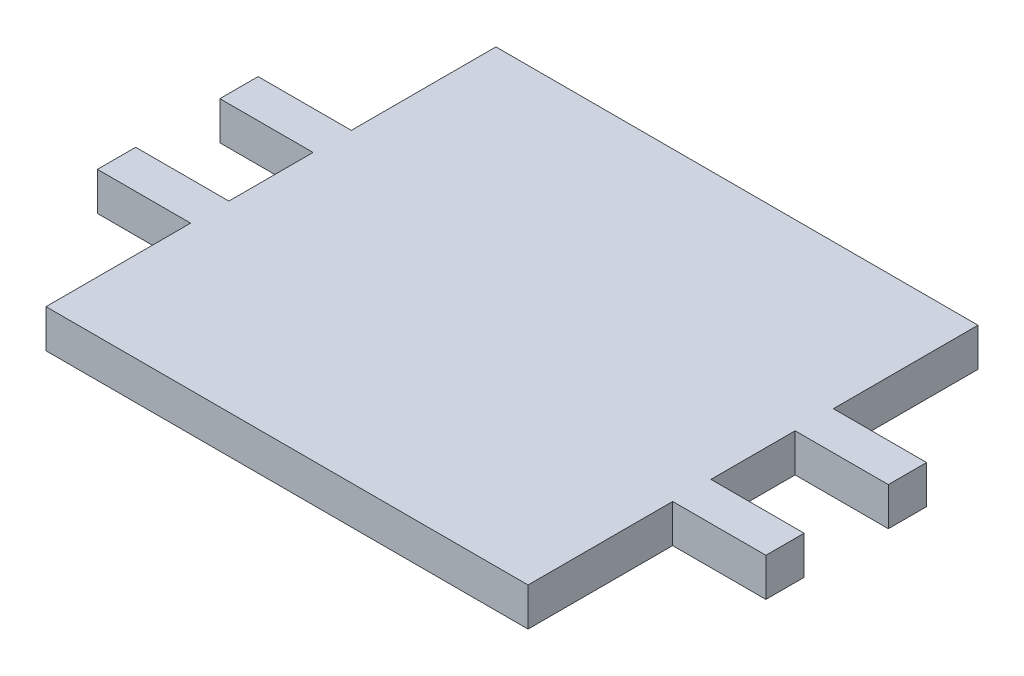
SolidWorks part; units mm, degrees
ref_plane "Front Plane" through (0, 0, 0) normal (0, 0, 1) x (1, 0, 0)
ref_plane "Top Plane" through (0, 0, 0) normal (0, 1, 0) x (1, 0, 0)
ref_plane "Right Plane" through (0, 0, 0) normal (1, 0, 0) x (0, 0, -1)
sketch "Sketch1" plane through (0, 0, 0) normal (0, 1, 0) x (1, 0, 0)
  line L0 (0, 35.56) -> (0, -35.56) construction
  line L1 (-38.1, 35.56) -> (38.1, 35.56)
  line L2 (-38.1, 35.56) -> (-38.1, -35.56)
  line L3 (-38.1, -35.56) -> (38.1, -35.56)
  line L4 (38.1, 35.56) -> (38.1, -35.56)
  line L5 (-38.1, 0) -> (38.1, 0) construction
  line L6 (-52.832, 6.6548) -> (-52.832, -6.6548) construction
  line L7 (-52.832, 12.7) -> (-38.1, 12.7)
  line L8 (-52.832, 12.7) -> (-52.832, 6.6548)
  line L9 (-52.832, 6.6548) -> (-38.1, 6.6548)
  line L10 (-38.1, 12.7) -> (-38.1, 6.6548)
  line L11 (-52.832, -6.6548) -> (-38.1, -6.6548)
  line L12 (-52.832, -6.6548) -> (-52.832, -12.7)
  line L13 (-52.832, -12.7) -> (-38.1, -12.7)
  line L14 (-38.1, -6.6548) -> (-38.1, -12.7)
  line L15 (52.832, -12.7) -> (38.1, -12.7)
  line L16 (38.1, -6.6548) -> (38.1, -12.7)
  line L17 (52.832, -6.6548) -> (38.1, -6.6548)
  line L18 (52.832, -6.6548) -> (52.832, -12.7)
  line L19 (52.832, 6.6548) -> (38.1, 6.6548)
  line L20 (38.1, 12.7) -> (38.1, 6.6548)
  line L21 (52.832, 12.7) -> (38.1, 12.7)
  line L22 (52.832, 12.7) -> (52.832, 6.6548)
  point P4 (0, 35.56)
  point P6 (-38.1, 0)
  point P19 (-52.832, 0)
  dimension "D1" = 76.2
  dimension "D2" = 71.12
  dimension "D3" = 14.732
  dimension "D4" = 6.0452
  dimension "D5" = 14.732
  dimension "D6" = 6.0452
  dimension "D7" = 25.4
extrude "Boss-Extrude1" add sketch "Sketch1" along normal blind 6.0452 contours L4 L1 L2 L3 | L12 L13 L2 L11 | L8 L9 L2 L7 | L22 L21 L4 L19 | L18 L17 L4 L15
